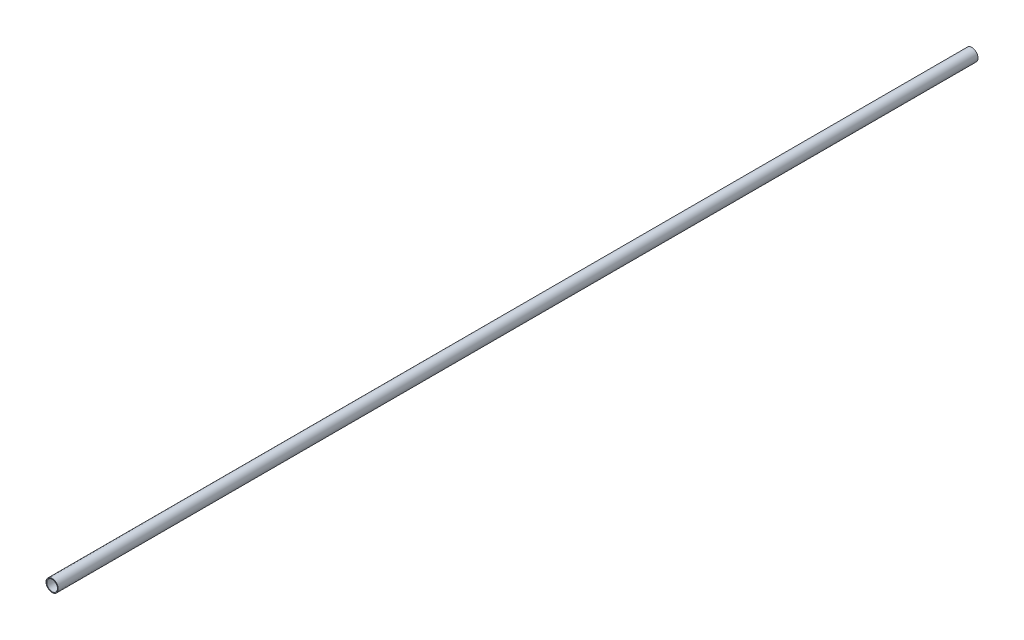
SolidWorks part; units mm, degrees
material "carbon fiber"
ref_plane "Front Plane" through (0, 0, 0) normal (0, 0, 1) x (1, 0, 0)
ref_plane "Top Plane" through (0, 0, 0) normal (0, 1, 0) x (1, 0, 0)
ref_plane "Right Plane" through (0, 0, 0) normal (1, 0, 0) x (0, 0, -1)
sketch "Эскиз1" plane through (0, 0, 0) normal (0, 0, 1) x (1, 0, 0)
  circle A0 centre (0, 0) radius 8
  circle A1 centre (0, 0) radius 7
  dimension "D1" = 16
  dimension "D2" = 1
extrude "Бобышка-Вытянуть1" add sketch "Эскиз1" along normal mid plane 1200
